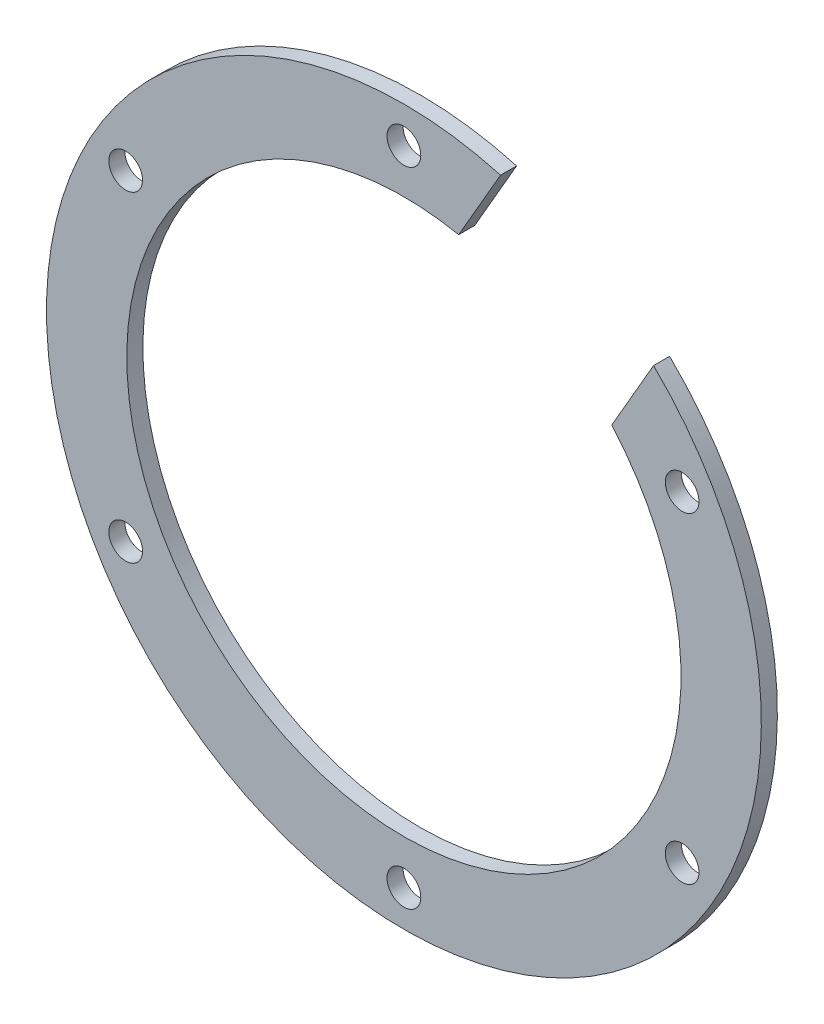
SolidWorks part; units mm, degrees
material "Thornel Mat VMA"
ref_plane "前视基准面" through (0, 0, 0) normal (0, 0, 1) x (1, 0, 0)
ref_plane "上视基准面" through (0, 0, 0) normal (0, 1, 0) x (1, 0, 0)
ref_plane "右视基准面" through (0, 0, 0) normal (1, 0, 0) x (0, 0, -1)
other "Configuration Table"
sketch "草图1" plane through (0, 0, 0) normal (0, 0, 1) x (1, 0, 0)
  circle A0 centre (0, 0) radius 34.5
  circle A1 centre (0, 0) radius 44.5
  dimension "D1" = 89
  dimension "D2" = 10
extrude "凸台-拉伸1" add sketch "草图1" along normal blind 2
sketch "草图2" plane through (0, 0, 2) normal (0, 0, 1) x (1, 0, 0)
  circle A0 centre (0, 0) radius 40 construction
  circle A1 centre (0, 40) radius 2.1
  circle A2 centre (34.641, 20) radius 2.1
  circle A3 centre (34.641, -20) radius 2.1
  circle A4 centre (0, -40) radius 2.1
  circle A5 centre (-34.641, -20) radius 2.1
  circle A6 centre (-34.641, 20) radius 2.1
  point P17 (0, 0)
  dimension "D1" = 80
  dimension "D2" = 4.2
  dimension "D3" = 6
extrude "切除-拉伸1" cut sketch "草图2" against normal blind 26
sketch "草图3" plane through (0, 0, 2) normal (0, 0, 1) x (1, 0, 0)
  line L0 (26.9193, 46.6255) -> (0, 0) construction
  line L1 (0, 0) -> (0, 44.5) construction
  line L2 (-6.056, 11.5106) -> (15.4274, 48.7211)
  line L3 (-6.056, 11.5106) -> (12.9965, 0.5106)
  line L4 (15.4274, 48.7211) -> (34.48, 37.7211)
  line L5 (12.9965, 0.5106) -> (34.48, 37.7211)
  line L6 (-6.056, 11.5106) -> (34.48, 37.7211) construction
  line L7 (15.4274, 48.7211) -> (12.9965, 0.5106) construction
  circle A0 centre (0, 0) radius 44.5 construction
  point P8 (14.212, 24.6159)
  dimension "D1" = 30
  dimension "D2" = 22
extrude "切除-拉伸2" cut sketch "草图3" against normal blind 26
